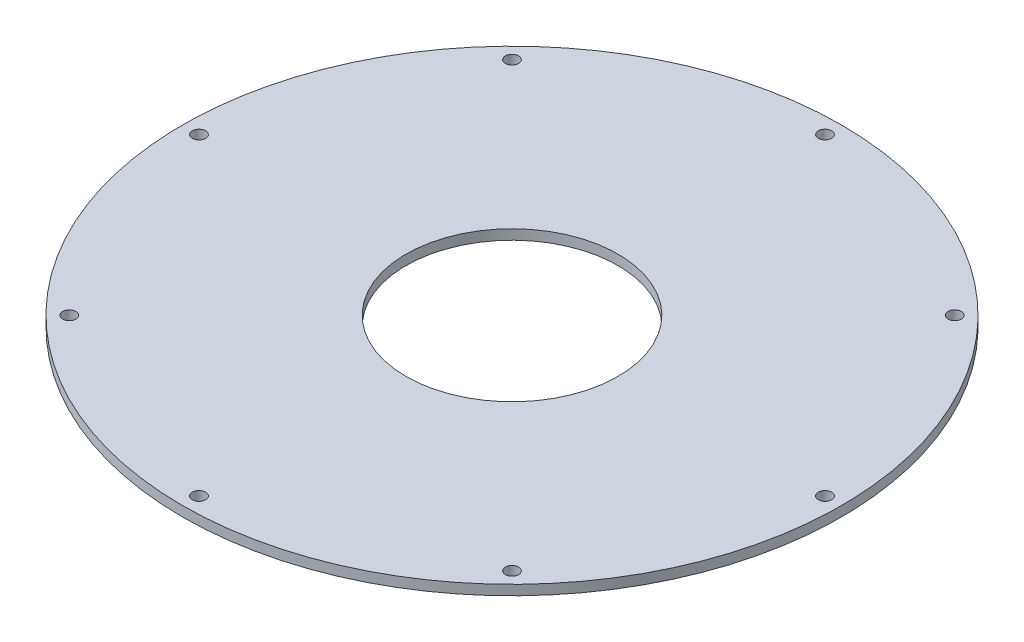
SolidWorks part; units mm, degrees
material "Thornel Mat VMA"
ref_plane "Front Plane" through (0, 0, 0) normal (0, 0, 1) x (1, 0, 0)
ref_plane "Top Plane" through (0, 0, 0) normal (0, 1, 0) x (1, 0, 0)
ref_plane "Right Plane" through (0, 0, 0) normal (1, 0, 0) x (0, 0, -1)
sketch "Sketch1" plane through (0, 0, 0) normal (0, 1, 0) x (1, 0, 0)
  circle A0 centre (0, 0) radius 32
  circle A1 centre (0, 0) radius 99.5
  dimension "D1" = 64
  dimension "D2" = 199
extrude "Base" add sketch "Sketch1" along normal mid plane 3
sketch "Sketch2" plane through (0, 1.5, 0) normal (0, 1, 0) x (1, 0, 0)
  line L0 (0, 96.5) -> (0, 99.5) construction
  circle A0 centre (0, 94.5) radius 2
  circle A1 centre (0, 0) radius 99.5 construction
  dimension "D1" = 4
  dimension "D2" = 3
extrude "Structural Hole" cut sketch "Sketch2" against normal through all
pattern_circular "Structural Hole Pattern" count 8 over 360 about axis through (0, 0, 0) along (0, 1, 0) of "Structural Hole"
equation "\"lift_fan_diameter\"=64"
equation "\"D1@Sketch1\"=\"lift_fan_diameter\""
equation "\"outer_diameter\"=199"
equation "\"D2@Sketch1\"=\"outer_diameter\""
equation "\"bolt_diameter\"=4"
equation "\"D1@Sketch2\"=\"bolt_diameter\""
equation "\"wall_thickness\"=3"
equation "\"D2@Sketch2\"=\"wall_thickness\""
